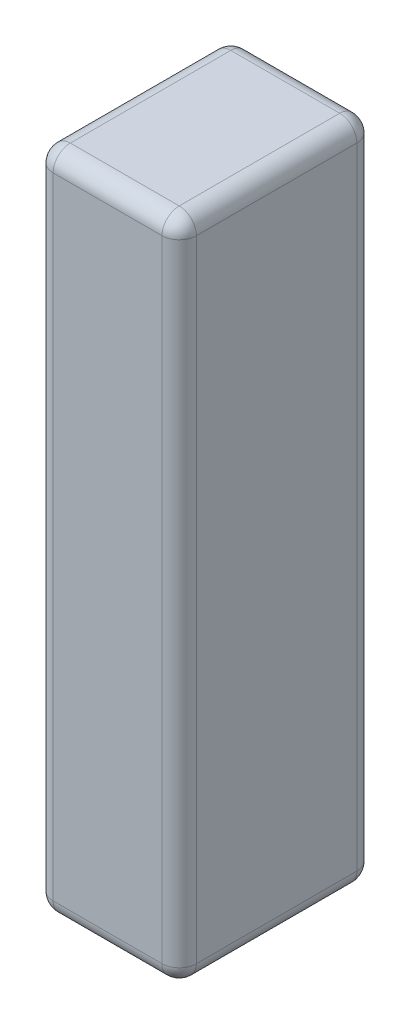
SolidWorks part; units mm, degrees
ref_plane "Front Plane" through (0, 0, 0) normal (0, 0, 1) x (1, 0, 0)
ref_plane "Top Plane" through (0, 0, 0) normal (0, 1, 0) x (1, 0, 0)
ref_plane "Right Plane" through (0, 0, 0) normal (1, 0, 0) x (0, 0, -1)
sketch "Sketch1" plane through (0, 0, 0) normal (0, 1, 0) x (1, 0, 0)
  line L1 (12.5, 17) -> (-12.5, 17)
  line L2 (12.5, 17) -> (12.5, -17)
  line L3 (12.5, -17) -> (-12.5, -17)
  line L4 (-12.5, 17) -> (-12.5, -17)
  line L5 (0, -17) -> (0, 17) construction
  line L6 (12.5, 0) -> (-12.5, 0) construction
  point P0 (0, 0)
  dimension "D1" = 34
  dimension "D2" = 25
extrude "Boss-Extrude1" add sketch "Sketch1" along normal blind 116
fillet "Fillet1" radius 3 12 edges at (-12.5, 58, -17) (-12.5, 58, 17) (12.5, 58, 17) (12.5, 58, -17) (0, 0, 17) (12.5, 0, 0) (0, 0, -17) (-12.5, 0, 0) (0, 116, -17) (12.5, 116, 0) (0, 116, 17) (-12.5, 116, 0)
